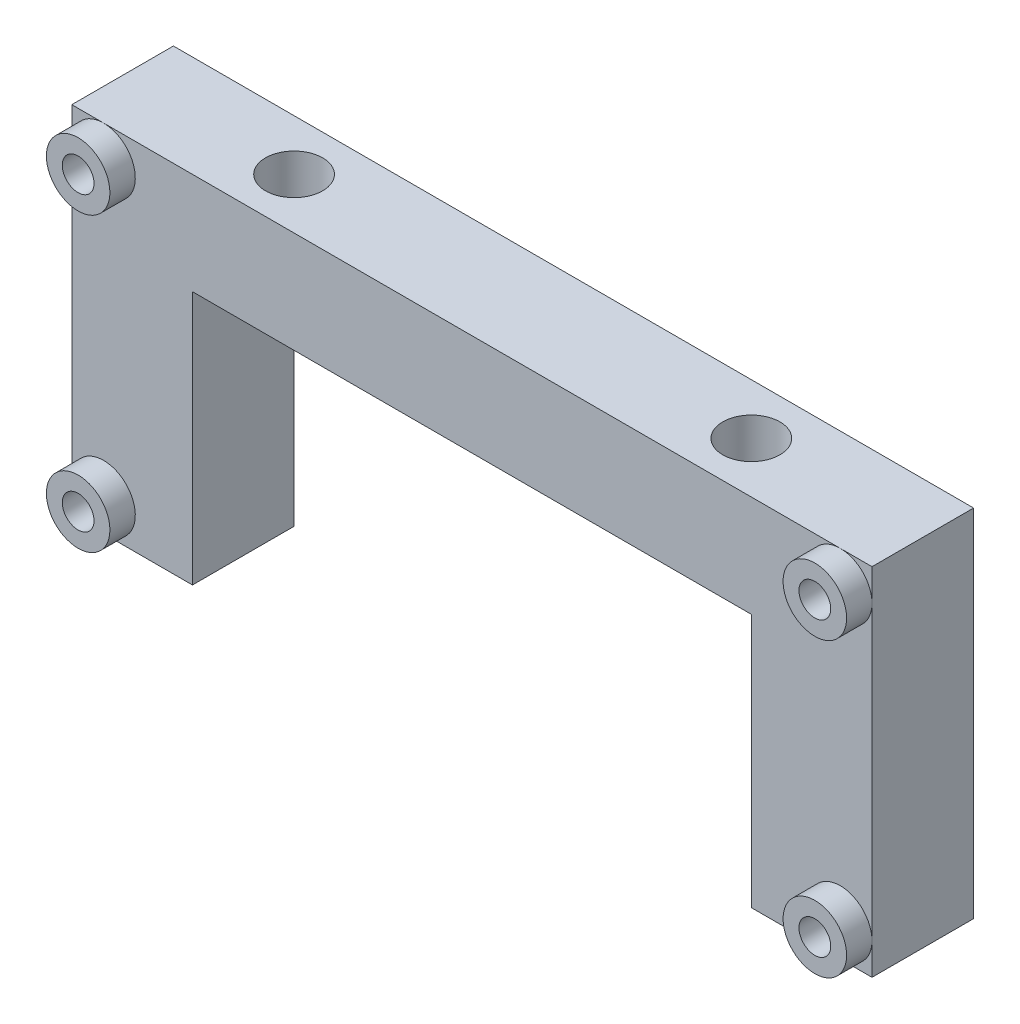
SolidWorks part; units mm, degrees
ref_plane "Piano frontale" through (0, 0, 0) normal (0, 0, 1) x (1, 0, 0)
ref_plane "Piano superiore" through (0, 0, 0) normal (0, 1, 0) x (1, 0, 0)
ref_plane "Piano destro" through (0, 0, 0) normal (1, 0, 0) x (0, 0, -1)
sketch "Schizzo1" plane through (0, 0, 0) normal (0, 0, 1) x (1, 0, 0)
  line L0 (0, 0) -> (0, 55)
  line L1 (0, 55) -> (44, 55)
  line L2 (44, 55) -> (44, 0)
  line L3 (44, 0) -> (36, 0)
  line L4 (36, 8) -> (36, 47)
  line L5 (36, 47) -> (8, 47)
  line L6 (8, 47) -> (8, 8)
  line L7 (8, 0) -> (0, 0)
  line L8 (8, 0) -> (36, 0)
  line L9 (8, 8) -> (36, 8)
  dimension "D1" = 8
  dimension "D2" = 8
  dimension "D3" = 8
  dimension "D4" = 44
  dimension "D5" = 55
  dimension "D6" = 8
extrude "Estrusione-Estrusione1" add sketch "Schizzo1" along normal blind 8
sketch "Schizzo2" plane through (0, 0, 0) normal (0, -1, 0) x (1, 0, 0)
  line L0 (0, 8) -> (8, 0) construction
  line L1 (36, 8) -> (44, 0) construction
  circle A0 centre (4, 4) radius 1.75
  circle A1 centre (40, 4) radius 1.75
  dimension "D1" = 3.5
  dimension "D2" = 3.5
extrude "Taglio-Estrusione1" cut sketch "Schizzo2" against normal blind 20
sketch "Schizzo3" plane through (0, 0, 8) normal (0, 0, 1) x (1, 0, 0)
  line L0 (44, 55) -> (0, 55) construction
  line L1 (-9.5, 55) -> (53.5, 55)
  line L2 (-9.5, 55) -> (-9.5, 27)
  line L3 (-9.5, 27) -> (8, 27)
  line L4 (53.5, 55) -> (53.5, 27)
  line L5 (8, 47) -> (36, 47) construction
  line L6 (8, 47) -> (36, 47)
  line L7 (36, 47) -> (36, 27)
  line L9 (8, 47) -> (8, 27)
  line L11 (36, 27) -> (53.5, 27)
  point P6 (22, 47)
  dimension "D1" = 63
  dimension "D2" = 31.5
  dimension "D3" = 28
extrude "Estrusione-Estrusione2" add sketch "Schizzo3" against normal blind 8
sketch "Schizzo4" plane through (0, 0, 8) normal (0, 0, 1) x (1, 0, 0)
  line L0 (53.5, 55) -> (-9.5, 55) construction
  line L1 (-7, 52.5) -> (51, 52.5) construction
  line L2 (-7, 52.5) -> (-7, 29.5) construction
  line L3 (-7, 29.5) -> (51, 29.5) construction
  line L4 (51, 52.5) -> (51, 29.5) construction
  line L5 (8, 47) -> (36, 47) construction
  circle A0 centre (-7, 52.5) radius 1.25
  circle A1 centre (51, 52.5) radius 1.25
  circle A2 centre (51, 29.5) radius 1.25
  circle A3 centre (-7, 29.5) radius 1.25
  circle A4 centre (-7, 52.5) radius 2.5
  circle A5 centre (-7, 29.5) radius 2.5
  circle A6 centre (51, 29.5) radius 2.5
  circle A7 centre (51, 52.5) radius 2.5
  point P14 (22, 47)
  dimension "D3" = 2.5
  dimension "D4" = 5
  dimension "D5" = 2.5
  dimension "D6" = 5
  dimension "D7" = 2.5
  dimension "D8" = 5
  dimension "D9" = 2.5
  dimension "D10" = 5
  dimension "D1" = 23
  dimension "D2" = 58
  dimension "D11" = 2.5
  dimension "D12" = 29
extrude "Estrusione-Estrusione3" add sketch "Schizzo4" along normal blind 2
sketch "Schizzo5" plane through (0, 0, 8) normal (0, 0, 1) x (1, 0, 0)
  circle A0 centre (-7, 52.5) radius 1.25
  circle A1 centre (-7, 29.5) radius 1.25
  circle A2 centre (51, 52.5) radius 1.25
  circle A3 centre (51, 29.5) radius 1.25
extrude "Taglio-Estrusione2" cut sketch "Schizzo5" against normal through all
sketch "Schizzo6" plane through (0, 0, 8) normal (0, 0, 1) x (1, 0, 0)
  line L0 (36, 8) -> (36, 47) construction
  line L1 (8, 47) -> (36, 47)
  line L2 (8, 47) -> (8, 55)
  line L3 (8, 55) -> (36, 55)
  line L4 (36, 47) -> (36, 55)
  line L5 (51, 55) -> (-7, 55) construction
extrude "Taglio-Estrusione3" cut sketch "Schizzo6" against normal blind 10
sketch "Schizzo7" plane through (0, 0, 8) normal (0, 0, 1) x (1, 0, 0)
  line L0 (36, 8) -> (36, 55) construction
  line L1 (8, 55) -> (36, 55)
  line L2 (8, 55) -> (8, 47)
  line L3 (8, 47) -> (36, 47)
  line L4 (36, 55) -> (36, 47)
  dimension "D1" = 8
extrude "Estrusione-Estrusione4" add sketch "Schizzo7" against normal blind 8
sketch "Schizzo8" plane through (0, 0, 8) normal (0, 0, 1) x (1, 0, 0)
  line L0 (44, 0) -> (44, 27) construction
  line L1 (0, 0) -> (44, 0)
  line L2 (0, 0) -> (0, 47)
  line L3 (0, 47) -> (44, 47)
  line L4 (44, 0) -> (44, 47)
  line L5 (8, 47) -> (36, 47) construction
extrude "Taglio-Estrusione4" cut sketch "Schizzo8" against normal blind 8
sketch "Schizzo9" plane through (0, 47, 0) normal (0, -1, 0) x (1, 0, 0)
  line L0 (0, 4) -> (44, 4) construction
  line L1 (0, 0) -> (0, 8) construction
  line L2 (44, 0) -> (44, 8) construction
  circle A0 centre (4, 4) radius 2.25
  circle A1 centre (40, 4) radius 2.25
  dimension "D3" = 4.5
  dimension "D4" = 4.5
  dimension "D1" = 4
  dimension "D2" = 4
extrude "Taglio-Estrusione5" cut sketch "Schizzo9" against normal blind 8
